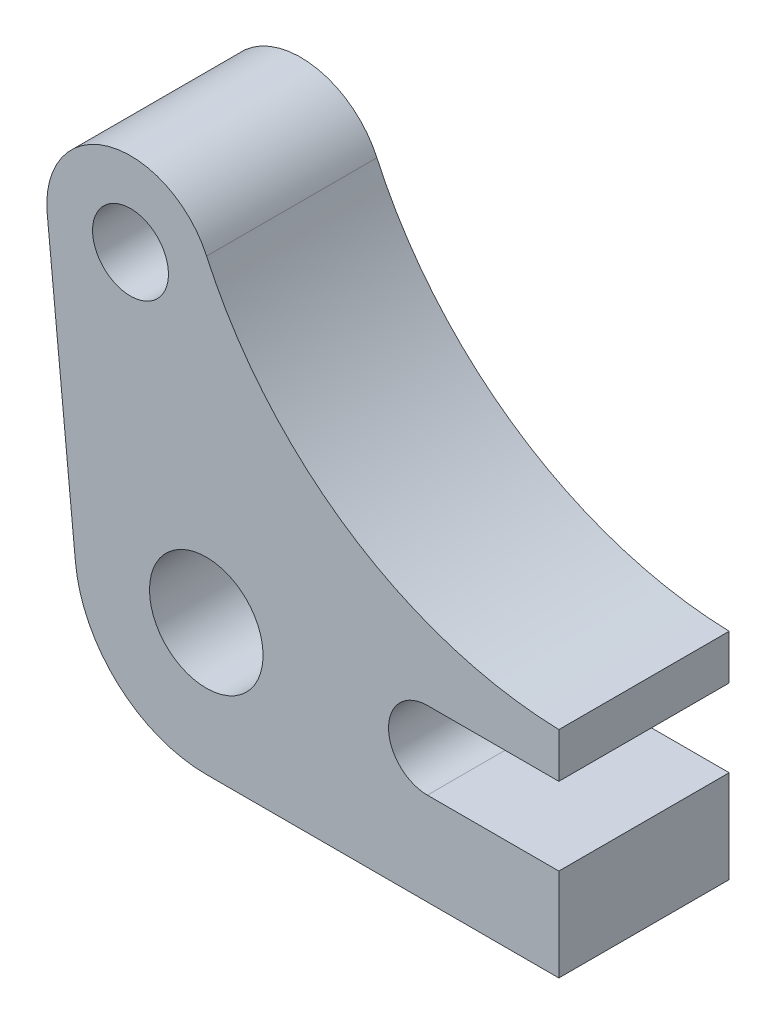
SolidWorks part; units mm, degrees
material "AISI 1020"
ref_plane "Plan de face" through (0, 0, 0) normal (0, 0, 1) x (1, 0, 0)
ref_plane "Plan de dessus" through (0, 0, 0) normal (0, 1, 0) x (1, 0, 0)
ref_plane "Plan de droite" through (0, 0, 0) normal (1, 0, 0) x (0, 0, -1)
sketch "Esquisse1" plane through (0, 0, 0) normal (0, 0, 1) x (1, 0, 0)
  line L3 (26.8166, -41.5335) -> (-32.1834, -41.5335)
  line L4 (-44.8655, 27.7969) -> (-32.1834, -19.5335) construction
  line L5 (-32.1834, -19.5335) -> (-32.1834, -2.1336) construction
  line L6 (26.8166, -5.5335) -> (26.8166, -41.5335)
  line L7 (26.8166, -19.5335) -> (4.8166, -19.5335) construction
  line L10 (26.8166, -26.0335) -> (4.8166, -26.0335)
  line L11 (26.8166, -13.0335) -> (4.8166, -13.0335)
  line L12 (-32.1834, -19.5335) -> (15.8166, -19.5335) construction
  line L13 (-58.7986, 26.4299) -> (-54.0782, -21.6816)
  arc A0 (26.8166, -5.5335) -> (-32.13, 33.6112) centre (28.8188, 61.4366) cw
  arc A1 (-32.13, 33.6112) -> (-58.7986, 26.4299) centre (-44.8655, 27.7969) ccw
  circle A4 centre (-44.8655, 27.7969) radius 6.35
  circle A5 centre (-32.1834, -19.5335) radius 9.5
  arc A8 (26.8166, -26.0335) -> (26.8166, -13.0335) centre (26.8166, -19.5335) ccw
  arc A9 (4.8166, -13.0335) -> (4.8166, -26.0335) centre (4.8166, -19.5335) ccw
  arc A10 (-32.1834, -41.5335) -> (-54.0782, -21.6816) centre (-32.1834, -19.5335) cw
  point P14 (15.8166, -19.5335)
  point P19 (0, 0)
  point P20 (0, 0)
  dimension "D2" = 67
  dimension "D3" = 14
  dimension "D8" = 12.7
  dimension "D9" = 22
  dimension "D10" = 19
  dimension "D11" = 6.5
  dimension "D1" = 49
  dimension "D5" = 15
  dimension "D6" = 36
  dimension "D4" = 22
  dimension "D7" = 22
  dimension "D12" = 59
extrude "Boss.-Extru.3" add sketch "Esquisse1" along normal blind 28.5 contours A10 L3 L6 L10 A9 L11 A0 A1 L13 A5 A4
equation "\"A\"= 59"
equation "\"B\"= 22"
equation "\"C\"= 28.5"
equation "\"D4@Esquisse1\"=\"B\""
equation "\"D9@Esquisse1\"=\"B\""
equation "\"D12@Esquisse1\"=\"A\""
